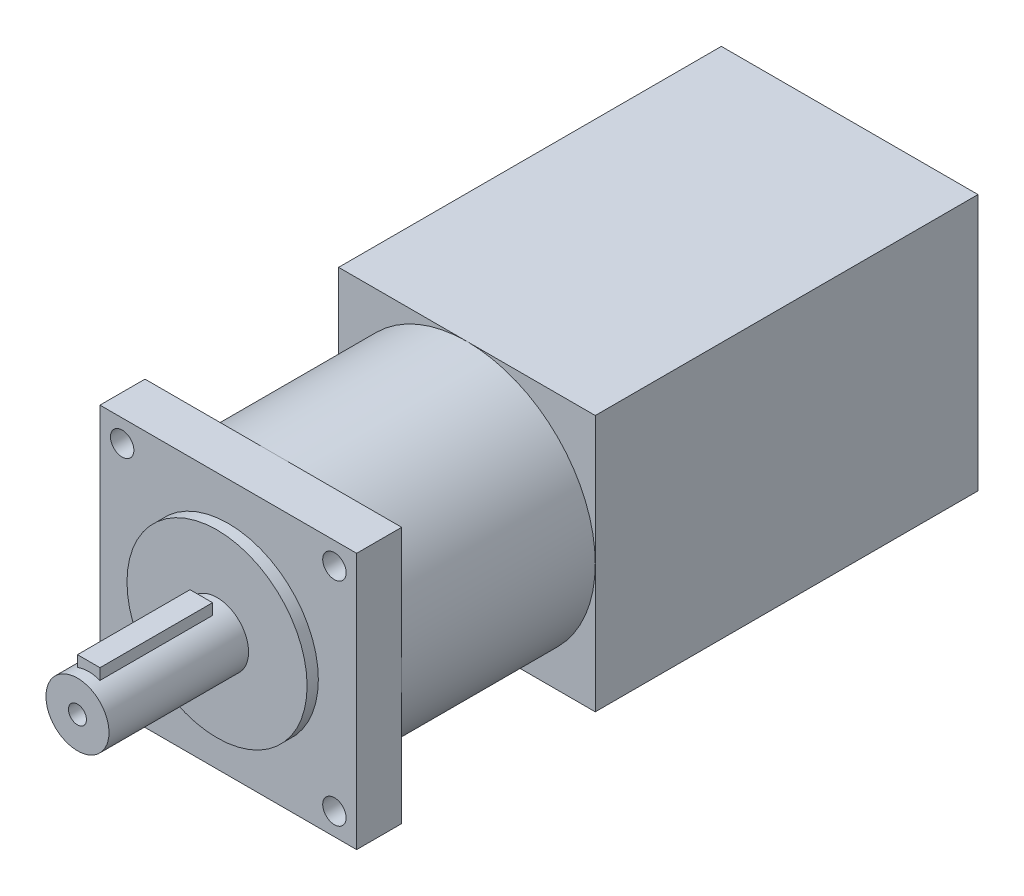
SolidWorks part; units mm, degrees
ref_plane "前视基准面" through (0, 0, 0) normal (0, 0, 1) x (1, 0, 0)
ref_plane "上视基准面" through (0, 0, 0) normal (0, 1, 0) x (1, 0, 0)
ref_plane "右视基准面" through (0, 0, 0) normal (1, 0, 0) x (0, 0, -1)
sketch "草图1" plane through (0, 0, 0) normal (0, 0, 1) x (1, 0, 0)
  line L1 (-28.5, 28.5) -> (28.5, 28.5)
  line L2 (-28.5, 28.5) -> (-28.5, -28.5)
  line L3 (-28.5, -28.5) -> (28.5, -28.5)
  line L4 (28.5, 28.5) -> (28.5, -28.5)
  line L5 (-28.5, 28.5) -> (28.5, -28.5) construction
  line L6 (-28.5, -28.5) -> (28.5, 28.5) construction
  point P0 (0, 0)
  dimension "D1" = 57
extrude "凸台-拉伸1" add sketch "草图1" along normal blind 85
sketch "草图2" plane through (0, 0, 85) normal (0, 0, 1) x (1, 0, 0)
  circle A0 centre (0, 0) radius 28.5
  dimension "D1" = 57
extrude "凸台-拉伸2" add sketch "草图2" along normal blind 53
sketch "草图3" plane through (0, 0, 138) normal (0, 0, 1) x (1, 0, 0)
  circle A0 centre (0, 0) radius 20
  dimension "D1" = 40
extrude "凸台-拉伸3" add sketch "草图3" along normal blind 2.5
sketch "草图4" plane through (0, 0, 140.5) normal (0, 0, 1) x (1, 0, 0)
  circle A0 centre (0, 0) radius 7
  dimension "D1" = 14
extrude "凸台-拉伸4" add sketch "草图4" along normal blind 31
sketch "草图7" plane through (0, 0, 138) normal (0, 0, 1) x (1, 0, 0)
  line L0 (-23.57, 23.57) -> (23.57, 23.57) construction
  line L1 (-28.5, -28.5) -> (28.5, -28.5)
  line L2 (-28.5, -28.5) -> (-28.5, 28.5)
  line L3 (-28.5, 28.5) -> (28.5, 28.5)
  line L4 (28.5, -28.5) -> (28.5, 28.5)
  line L5 (-28.5, -28.5) -> (28.5, 28.5) construction
  line L6 (-28.5, 28.5) -> (28.5, -28.5) construction
  circle A0 centre (-23.57, 23.57) radius 2.6
  circle A1 centre (23.57, 23.57) radius 2.6
  circle A2 centre (23.57, -23.57) radius 2.6
  circle A3 centre (-23.57, -23.57) radius 2.6
  point P0 (0, 0)
  dimension "D3" = 5.2
  dimension "D1" = 57
  dimension "D2" = 47.14
extrude "凸台-拉伸5" add sketch "草图7" against normal blind 10
ref_plane "基准面1" through (0, 0, 169) normal (0, 0, 1) x (1, 0, 0)
sketch "草图8" plane through (0, 0, 169) normal (0, 0, 1) x (1, 0, 0)
  line L1 (2.5, 5) -> (-2.5, 5)
  line L2 (2.5, 5) -> (2.5, 9)
  line L3 (2.5, 9) -> (-2.5, 9)
  line L4 (-2.5, 5) -> (-2.5, 9)
  line L5 (2.5, 5) -> (-2.5, 9) construction
  line L6 (2.5, 9) -> (-2.5, 5) construction
  circle A0 centre (0, 0) radius 7 construction
  circle A1 centre (0, 0) radius 7 construction
  point P0 (0, 7)
  dimension "D1" = 5
  dimension "D2" = 4
extrude "凸台-拉伸6" add sketch "草图8" against normal blind 25
sketch "草图9" plane through (0, 0, 171.5) normal (0, 0, 1) x (1, 0, 0)
  circle A0 centre (0, 0) radius 2
  dimension "D1" = 4
extrude "切除-拉伸1" cut sketch "草图9" against normal blind 6
